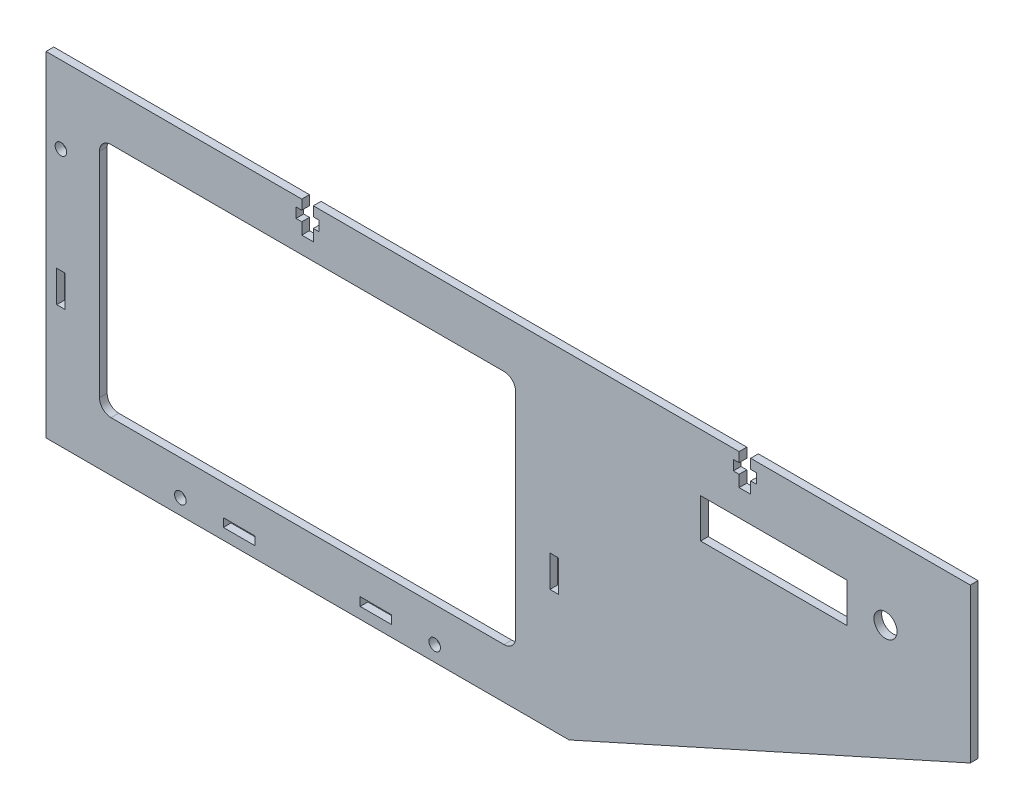
SolidWorks part; units mm, degrees
ref_plane "前视基准面" through (0, 0, 0) normal (0, 0, 1) x (1, 0, 0)
ref_plane "上视基准面" through (0, 0, 0) normal (0, 1, 0) x (1, 0, 0)
ref_plane "右视基准面" through (0, 0, 0) normal (1, 0, 0) x (0, 0, -1)
sketch "草图1" plane through (0, 0, 0) normal (0, 0, 1) x (1, 0, 0)
  line L0 (21.5651, -10.096) -> (13.5651, -8.096) construction
  line L1 (32.8151, -9.096) -> (-33.1849, -9.096) construction
  line L3 (-34.6849, -10.096) -> (-31.6849, -8.096) construction
  line L4 (-21.9349, -10.096) -> (-13.9349, -8.096) construction
  line L5 (-22.0349, -10.196) -> (-13.8349, -10.196)
  line L6 (-13.8349, -7.996) -> (-13.8349, -10.196)
  line L7 (-22.0349, -7.996) -> (-13.8349, -7.996)
  line L8 (-22.0349, -7.996) -> (-22.0349, -10.196)
  line L12 (-52.1849, -13.096) -> (-18.9349, -13.096)
  line L13 (64.9151, 18.2415) -> (62.7151, 18.2415)
  line L15 (34.3151, -10.096) -> (31.3151, -8.096) construction
  line L16 (21.6651, -7.996) -> (21.6651, -10.196)
  line L17 (21.6651, -7.996) -> (13.4651, -7.996)
  line L18 (13.4651, -7.996) -> (13.4651, -10.196)
  line L19 (67.6951, -13.096) -> (18.5651, -13.096)
  line L20 (64.9151, 18.2415) -> (64.9151, 26.4415)
  line L21 (-18.9349, -13.096) -> (18.5651, -13.096)
  line L22 (64.9151, 26.4415) -> (62.7151, 26.4415)
  line L25 (-63.0849, 18.2415) -> (-63.0849, 26.4415)
  line L26 (-65.2849, 26.4415) -> (-63.0849, 26.4415)
  line L27 (-65.2849, 18.2415) -> (-65.2849, 26.4415)
  line L28 (-65.2849, 18.2415) -> (-63.0849, 18.2415)
  line L29 (21.6651, -10.196) -> (13.4651, -10.196)
  line L34 (62.7151, 18.2415) -> (62.7151, 26.4415)
  line L35 (-52.1849, -13.096) -> (-68.0618, -13.096)
  line L41 (-49.1849, 53.779) -> (-49.1849, 33.779) construction
  line L42 (-49.1849, 53.779) -> (-49.1849, 73.779) construction
  line L43 (-68.0618, -13.096) -> (-68.0618, 73.779)
  line L46 (-49.1849, 53.779) -> (237.809, 53.779) construction
  line L47 (54.8151, 73.779) -> (54.8151, 87.1175) construction
  line L48 (54.8151, 87.1175) -> (171.8151, 87.1175) construction
  line L49 (-49.1849, 33.779) -> (206.8345, 33.779) construction
  line L50 (113.3151, 87.1175) -> (113.3151, 11.0003) construction
  line L51 (54.8151, 87.1175) -> (-62.1849, 87.1175) construction
  line L52 (-0.1849, -9.096) -> (-0.1849, 138.1567) construction
  line L53 (-1.6849, 71.279) -> (-3.1849, 71.279)
  line L59 (67.6951, -13.096) -> (171.8151, 33.779)
  line L60 (171.8151, 73.779) -> (171.8151, 33.779)
  line L61 (1.3151, 71.279) -> (2.8151, 71.279)
  line L62 (1.3151, 73.779) -> (1.3151, 71.279)
  line L63 (-3.1849, 71.279) -> (-3.1849, 68.679)
  line L64 (-3.1849, 68.679) -> (-1.6849, 68.679)
  line L65 (-1.6849, 68.679) -> (-1.6849, 65.679)
  line L66 (1.3151, 65.679) -> (-1.6849, 65.679)
  line L67 (1.3151, 68.679) -> (1.3151, 65.679)
  line L68 (2.8151, 68.679) -> (1.3151, 68.679)
  line L69 (2.8151, 71.279) -> (2.8151, 68.679)
  line L70 (-1.6849, 71.279) -> (-1.6849, 73.779)
  line L71 (-68.0618, 73.779) -> (-1.6849, 73.779)
  line L73 (-0.1849, 73.779) -> (-0.1849, 71.279) construction
  line L74 (139.8151, 53.779) -> (149.8151, 53.779) construction
  line L76 (114.8151, 73.779) -> (171.8151, 73.779)
  line L77 (111.8151, 71.279) -> (110.3151, 71.279)
  line L78 (114.8151, 71.279) -> (116.3151, 71.279)
  line L79 (114.8151, 73.779) -> (114.8151, 71.279)
  line L80 (110.3151, 71.279) -> (110.3151, 68.679)
  line L81 (110.3151, 68.679) -> (111.8151, 68.679)
  line L82 (111.8151, 68.679) -> (111.8151, 65.679)
  line L83 (114.8151, 65.679) -> (111.8151, 65.679)
  line L84 (114.8151, 68.679) -> (114.8151, 65.679)
  line L85 (116.3151, 68.679) -> (114.8151, 68.679)
  line L86 (116.3151, 71.279) -> (116.3151, 68.679)
  line L87 (111.8151, 71.279) -> (111.8151, 73.779)
  line L88 (114.8151, 65.679) -> (124.8151, 65.679) construction
  line L89 (113.3151, 73.779) -> (113.3151, 71.279) construction
  line L91 (1.3151, 73.779) -> (111.8151, 73.779)
  line L92 (124.8151, 53.779) -> (124.8151, 48.679) construction
  line L97 (124.8151, 48.679) -> (139.8151, 48.679)
  line L98 (139.8151, 48.679) -> (139.8151, 58.879)
  line L99 (139.8151, 58.879) -> (124.8151, 58.879)
  line L100 (111.8151, 65.679) -> (101.8151, 65.679) construction
  line L101 (101.8151, 58.879) -> (101.8151, 48.679)
  line L102 (101.8151, 48.679) -> (124.8151, 48.679)
  line L103 (124.8151, 58.879) -> (101.8151, 58.879)
  line L104 (-0.1849, 22.3415) -> (67.6951, 22.3415) construction
  line L105 (53.8151, 58.279) -> (53.8151, 2.904)
  line L106 (63.8151, 71.279) -> (-64.1849, 71.279) construction
  line L107 (63.8151, 71.279) -> (63.8151, -10.096) construction
  line L108 (63.8151, -10.096) -> (-64.1849, -10.096) construction
  line L109 (-64.1849, 71.279) -> (-64.1849, -10.096) construction
  line L110 (50.8151, -0.096) -> (-51.1849, -0.096)
  line L111 (-54.1849, 58.279) -> (-54.1849, 2.904)
  line L112 (50.8151, 61.279) -> (-51.1849, 61.279)
  line L113 (53.8151, -0.096) -> (-54.1849, -0.096) construction
  line L114 (53.8151, 61.279) -> (53.8151, -0.096) construction
  line L115 (-54.1849, 61.279) -> (-54.1849, -0.096) construction
  line L116 (53.8151, 61.279) -> (-54.1849, 61.279) construction
  circle A0 centre (-33.1849, -9.096) radius 1.5
  circle A2 centre (32.8151, -9.096) radius 1.5
  circle A11 centre (149.8151, 53.779) radius 3
  arc A12 (50.8151, -0.096) -> (53.8151, 2.904) centre (50.8151, 2.904) ccw
  arc A13 (-51.1849, -0.096) -> (-54.1849, 2.904) centre (-51.1849, 2.904) cw
  arc A14 (-54.1849, 58.279) -> (-51.1849, 61.279) centre (-51.1849, 58.279) cw
  arc A15 (50.8151, 61.279) -> (53.8151, 58.279) centre (50.8151, 58.279) cw
  circle A16 centre (-64.1849, 53.779) radius 1.5
  point P66 (-19.749, 73.5671)
  dimension "D1" = 10
  dimension "D2" = 3
extrude "凸台-拉伸1" add sketch "草图1" along normal blind 2 contours L12 L21 L19
sketch "草图3" plane through (0, 73.779, 0) normal (0, 1, 0) x (1, 0, 0)
  line L0 (-1.6849, -1) -> (1.3151, -1)
  line L1 (-1.6849, -2) -> (-1.6849, 0) construction
  line L2 (1.3151, -2) -> (1.3151, 0) construction
  line L3 (111.8151, -1) -> (114.8151, -1)
  line L4 (111.8151, -2) -> (111.8151, 0) construction
  line L5 (114.8151, -2) -> (114.8151, 0) construction
  circle A0 centre (-0.1849, -1) radius 1.5
  circle A1 centre (113.3151, -1) radius 1.5
